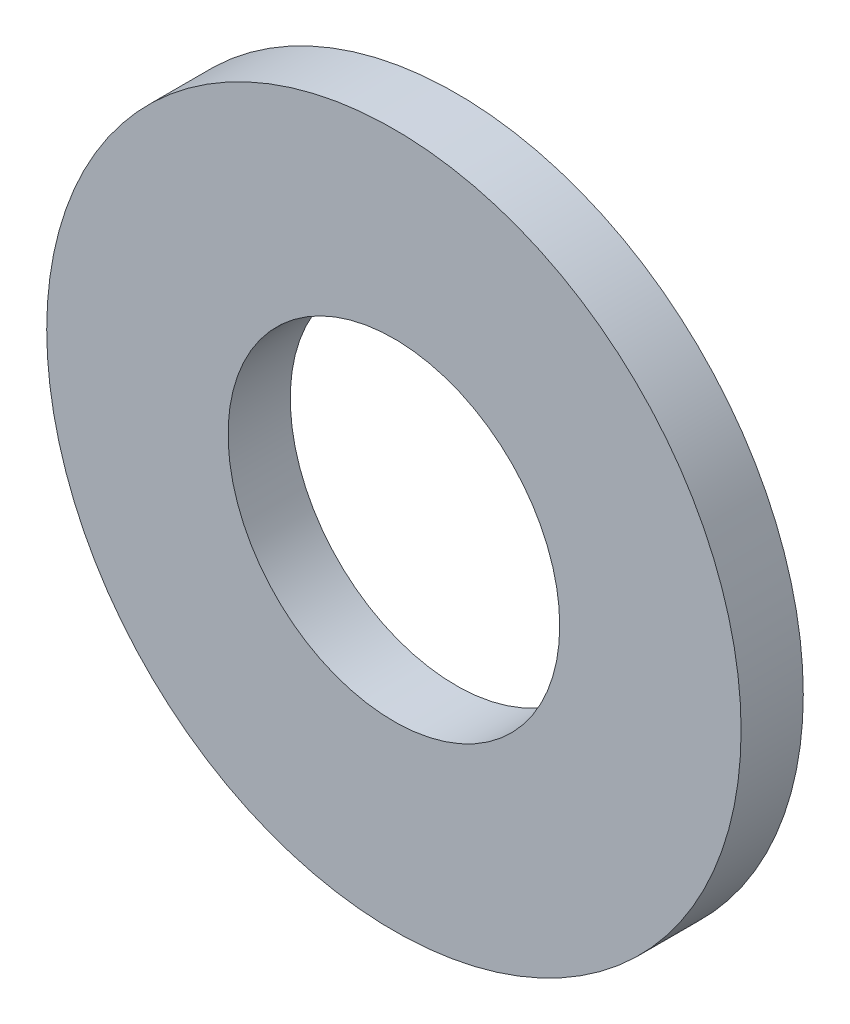
SolidWorks part; units mm, degrees
ref_plane "Front Plane" through (0, 0, 0) normal (0, 0, 1) x (1, 0, 0)
ref_plane "Top Plane" through (0, 0, 0) normal (0, 1, 0) x (1, 0, 0)
ref_plane "Right Plane" through (0, 0, 0) normal (1, 0, 0) x (0, 0, -1)
sketch "Sketch1" plane through (0, 0, 0) normal (0, 0, 1) x (1, 0, 0)
  circle A0 centre (0, 0) radius 3.35
  circle A1 centre (0, 0) radius 1.6
  dimension "OD" = 6.7
  dimension "ID1" = 3.2
extrude "Boss-Extrude1" add sketch "Sketch1" along normal blind 0.6
